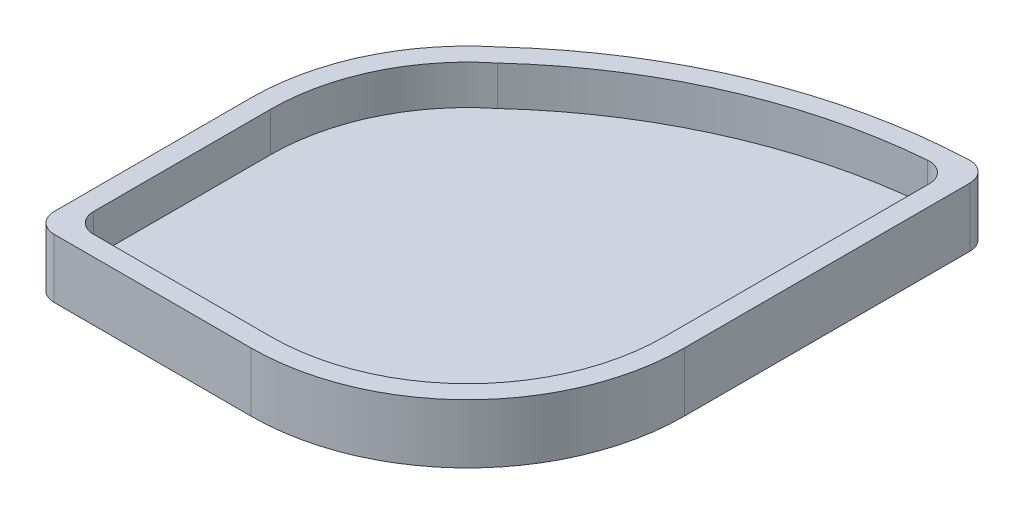
SolidWorks part; units mm, degrees
ref_plane "前基準面" through (0, 0, 0) normal (0, 0, 1) x (1, 0, 0)
ref_plane "上基準面" through (0, 0, 0) normal (0, 1, 0) x (1, 0, 0)
ref_plane "右基準面" through (0, 0, 0) normal (1, 0, 0) x (0, 0, -1)
sketch "草圖2" plane through (0, 0, 0) normal (0, 1, 0) x (1, 0, 0)
  circle A0 centre (0, 0) radius 55
  dimension "D1" = 110
extrude "填料-伸長1" add sketch "草圖2" along normal blind 15
sketch "草圖3" plane through (0, 15, 0) normal (0, 1, 0) x (1, 0, 0)
  circle A0 centre (0, 0) radius 50
  dimension "D1" = 100
extrude "除料-伸長1" cut sketch "草圖3" against normal blind 10
sketch "草圖8" plane through (0, 0, 0) normal (0, -1, 0) x (1, 0, 0)
  line L0 (0, 55) -> (-55, 55)
  line L1 (-55, 0) -> (-55, 55)
  line L2 (55, 0) -> (55, -77.6055)
  line L3 (55, 0) -> (55, 55) construction
  line L4 (0, 55) -> (55, 55) construction
  arc A0 (0, 55) -> (55, 0) centre (0, 0) ccw construction
  arc A1 (0, 55) -> (55, 0) centre (0, 0) ccw construction
  arc A2 (-42.7394, -34.6171) -> (55, -77.6055) centre (55, 55) ccw
  arc A3 (0, 55) -> (55, 0) centre (0, 0) ccw
  point P11 (55, 55)
  arc M2 (0, 55) -> (55, 0) centre (0, 0) ccw
extrude "填料-伸長3" add sketch "草圖8" against normal blind 15 contours A2 L2 M2 | L1 L0 M2
sketch "草圖9" plane through (0, 15, 0) normal (0, 1, 0) x (1, 0, 0)
  line L0 (55, 0) -> (55, 77.6055) construction
  line L1 (55, 0) -> (55, 77.6055)
  line L2 (50, 0) -> (50, 72.5075)
  line L3 (50, 0) -> (50, 72.5075) construction
  arc A0 (55, 77.6055) -> (-34.6171, 42.7394) centre (55, -55) ccw construction
  arc A1 (55, 77.6055) -> (-34.6171, 42.7394) centre (55, -55) ccw
  arc A2 (50, 72.5075) -> (-31.3526, 38.9489) centre (55, -55) ccw
  circle A3 centre (0, 0) radius 50 construction
  circle A4 centre (0, 0) radius 50
  arc A5 (50, 72.5075) -> (-31.238, 39.054) centre (55, -55) ccw construction
  circle M2 centre (0, 0) radius 50
  dimension "D1" = 5
extrude "除料-伸長4" cut sketch "草圖9" against normal blind 10 contours L2 A2 M2
sketch "草圖10" plane through (0, 15, 0) normal (0, 1, 0) x (1, 0, 0)
  line L4 (0, -50) -> (-50, -50)
  line L5 (-50, 0) -> (-50, -50)
  arc A0 (-31.3526, 38.9489) -> (50, 0) centre (0, 0) ccw construction
  arc A1 (-50, 0) -> (0, -50) centre (0, 0) ccw
extrude "除料-伸長5" cut sketch "草圖10" against normal blind 10
fillet "圓角1" radius 5 1 edges at (-50, 10, 50)
fillet "圓角2" radius 5 1 edges at (50, 10, -72.5075)
fillet "圓角3" radius 5 2 edges at (-55, 7.5, 55) (55, 7.5, -77.6055)
